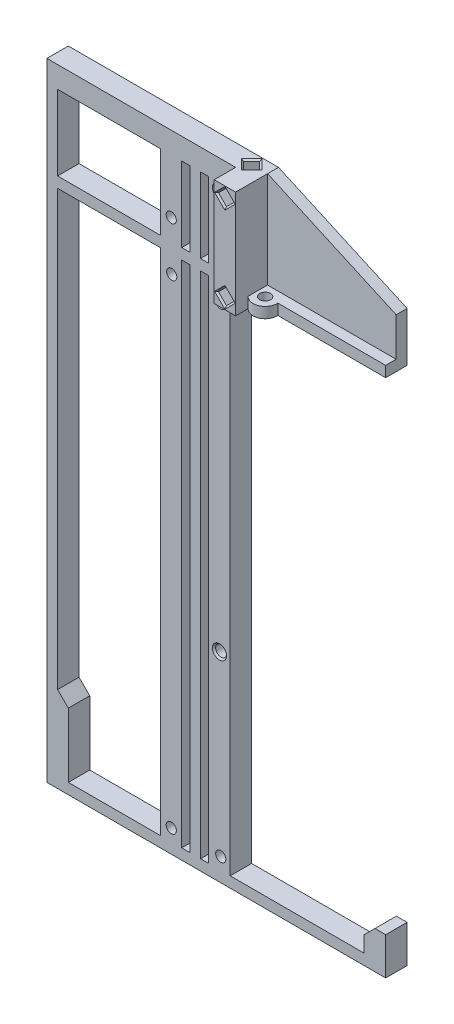
SolidWorks part; units mm, degrees
ref_plane "Front Plane" through (0, 0, 0) normal (0, 0, 1) x (1, 0, 0)
ref_plane "Top Plane" through (0, 0, 0) normal (0, 1, 0) x (1, 0, 0)
ref_plane "Right Plane" through (0, 0, 0) normal (1, 0, 0) x (0, 0, -1)
sketch "matx screw pattern" plane through (0, 0, 0) normal (0, 0, 1) x (1, 0, 0)
  line L1 (-121.92, 121.92) -> (121.92, 121.92) construction
  line L2 (-121.92, 121.92) -> (-121.92, -121.92) construction
  line L3 (-121.92, -121.92) -> (121.92, -121.92) construction
  line L4 (121.92, 121.92) -> (121.92, -121.92) construction
  point P4 (0, 121.92)
  point P6 (121.92, 0)
  point P7 (-111.76, -87.63)
  point P8 (-111.76, -41.91)
  point P9 (-88.9, 115.57)
  point P10 (43.18, -41.91)
  point P11 (43.18, -87.63)
  point P12 (43.18, -107.95)
  point P13 (115.57, -41.91)
  point P14 (115.57, 115.57)
  point P15 (43.18, 115.57)
  dimension "D1" = 243.84
  dimension "D2" = 10.16
  dimension "D3" = 22.86
  dimension "D4" = 227.33
  dimension "D5" = 154.94
  dimension "D6" = 203.2
  dimension "D7" = 45.72
  dimension "D8" = 20.32
  dimension "D9" = 34.29
sketch "Sketch1" plane through (0, 0, 0) normal (0, 0, 1) x (1, 0, 0)
  line L11 (47.4133, 127) -> (130.429, 127)
  line L12 (119.8033, 118.5333) -> (119.8033, 88.9)
  line L13 (181.229, -120.65) -> (47.4133, -120.65)
  line L14 (55.88, -116.4167) -> (55.88, -120.65) construction
  line L15 (55.88, -116.4167) -> (55.88, -91.0167)
  line L16 (51.6467, 118.5333) -> (92.1956, 118.5333)
  line L17 (51.6467, 118.5333) -> (51.6467, 88.9)
  line L18 (55.88, -116.4167) -> (92.1956, -116.4167)
  line L19 (111.3367, 118.5333) -> (111.3367, 88.9)
  line L20 (55.88, -91.0167) -> (51.6467, -86.7833)
  line L21 (119.8033, 118.5333) -> (121.9623, 118.5333)
  line L22 (121.9623, 118.5333) -> (121.9623, 88.9)
  line L26 (130.429, 127) -> (130.429, 88.9)
  line L27 (119.8033, -116.4167) -> (172.7623, -116.4167)
  line L29 (55.88, -116.4167) -> (47.4133, -116.4167) construction
  line L30 (47.4133, -120.65) -> (47.4133, 127)
  line L31 (172.7623, -116.4167) -> (172.7623, -110.0667)
  line L32 (172.7623, -110.0667) -> (176.9957, -105.8333)
  line L33 (92.1956, 118.5333) -> (92.1956, 88.9)
  line L34 (51.6467, 84.6667) -> (92.1956, 84.6667)
  line L35 (100.6623, -116.4167) -> (103.8828, -116.4167)
  line L36 (100.6623, 118.5333) -> (100.6623, 88.9)
  line L37 (100.6623, 118.5333) -> (103.8828, 118.5333)
  line L38 (100.6623, 84.6667) -> (103.8828, 84.6667)
  line L40 (119.8033, 84.6667) -> (181.229, 84.6667)
  line L41 (51.6467, 88.9) -> (92.1956, 88.9)
  line L42 (100.6623, 88.9) -> (103.8828, 88.9)
  line L43 (119.8033, 88.9) -> (121.9623, 88.9)
  line L44 (130.429, 88.9) -> (181.229, 88.9)
  line L45 (92.1956, -116.4167) -> (100.6623, -116.4167) construction
  line L46 (51.6467, 84.6667) -> (51.6467, -86.7833)
  line L47 (92.1956, 84.6667) -> (92.1956, -116.4167)
  line L48 (100.6623, 84.6667) -> (100.6623, -116.4167)
  line L49 (111.3367, 84.6667) -> (111.3367, -116.4167)
  line L50 (119.8033, 84.6667) -> (119.8033, -116.4167)
  line L54 (111.3367, -116.4167) -> (119.8033, -116.4167) construction
  line L55 (51.6467, 118.5333) -> (51.6467, 127) construction
  line L56 (172.7623, -116.4167) -> (181.229, -116.4167) construction
  line L57 (51.6467, -86.7833) -> (47.4133, -86.7833) construction
  line L58 (176.9957, -105.8333) -> (181.229, -105.8333)
  line L59 (51.6467, 88.9) -> (51.6467, 84.6667) construction
  line L60 (-121.92, 121.92) -> (121.92, 121.92) construction
  line L61 (121.9623, 88.9) -> (130.429, 88.9) construction
  line L62 (181.229, -105.8333) -> (181.229, -120.65)
  line L63 (103.8828, 118.5333) -> (103.8828, 88.9)
  line L64 (108.1161, 118.5333) -> (108.1161, 88.9)
  line L65 (108.1161, -116.4167) -> (111.3367, -116.4167)
  line L66 (108.1161, 88.9) -> (111.3367, 88.9)
  line L67 (108.1161, 84.6667) -> (111.3367, 84.6667)
  line L68 (103.8828, 84.6667) -> (103.8828, -116.4167)
  line L69 (108.1161, 84.6667) -> (108.1161, -116.4167)
  line L70 (108.1161, 118.5333) -> (111.3367, 118.5333)
  line L71 (103.8828, -116.4167) -> (108.1161, -116.4167) construction
  line L72 (181.229, 88.9) -> (181.229, 84.6667)
  point P0 (115.57, -116.4167)
  dimension "D2" = 4.2333
  dimension "D3" = 38.1
  dimension "D4" = 8.4667
  dimension "D5" = 4.2333
  dimension "D6" = 5.08
  dimension "D7" = 6.35
  dimension "D8" = 25.4
  dimension "D9" = 50.8
  dimension "D10" = 45
  dimension "D11" = 247.65
  dimension "D12" = 133.8157
  dimension "D13" = 40.549
extrude "Boss-Extrude1" add sketch "Sketch1" against normal blind 8.4667 from offset 9.525 offset against normal yes
sketch "Sketch9" plane through (0, 0, -17.9917) normal (0, 0, 1) x (1, 0, 0)
  line L3 (181.229, 88.9) -> (130.429, 88.9)
  line L4 (130.429, 127) -> (130.429, 88.9)
  line L7 (130.429, 127) -> (181.229, 104.14)
  line L9 (181.229, 104.14) -> (181.229, 88.9)
  dimension "D1" = 38.1
  dimension "D2" = 15.24
extrude "Boss-Extrude2" add sketch "Sketch9" along normal blind 4.318
sketch "Sketch16" plane through (0, 0, -9.525) normal (0, 0, 1) x (1, 0, 0)
  line L0 (119.8033, 84.6667) -> (181.229, 84.6667) construction
  line L1 (130.429, 127) -> (121.9623, 127)
  line L2 (130.429, 127) -> (130.429, 84.6667)
  line L3 (130.429, 84.6667) -> (121.9623, 84.6667)
  line L4 (121.9623, 127) -> (121.9623, 84.6667)
  line L5 (121.9623, 88.9) -> (121.9623, 118.5333) construction
extrude "Boss-Extrude3" add sketch "Sketch16" along normal blind 8.4667
sketch "Sketch18" plane through (0, 84.6667, 0) normal (0, -1, 0) x (-1, 0, 0)
  circle A0 centre (-133.889, 9.2517) radius 4.7625
  dimension "D1" = 9.525
extrude "Boss-Extrude4" add sketch "Sketch18" against normal up to surface (4.2333 mm away) up to face at (155.829, 88.9, -11.5993)
sketch "Sketch21" plane through (0, 88.9, 0) normal (0, 1, 0) x (1, 0, 0)
  arc A0 (130.429, 5.9791) -> (138.6436, 9.525) centre (133.889, 9.2517) ccw construction
  point P0 (133.889, 9.2517)
hole_wizard "#18 (0.1695) Diameter Hole3" positions "Sketch21" profile "Sketch22" hole size "#18" standard "ANSI Inch"
sketch "Sketch22" plane through (133.889, 88.9, -9.2517) normal (1, 0, 0) x (0, 0, 1)
  line L0 (0, 0) -> (0, 4.2333)
  line L1 (0, 4.2333) -> (2.1526, 4.2333)
  line L2 (2.1526, 4.2333) -> (2.1526, 0)
  line L5 (2.1526, 0) -> (0, 0)
  line L11 (0, -6.35) -> (0, 107.95) construction
  dimension "Thru Hole Dia." = 4.3053
  dimension "Thru Hole Depth" = 4.2333
sketch "Sketch5" plane through (0, 0, -9.525) normal (0, 0, 1) x (1, 0, 0)
  point P15 (115.57, 115.57)
  point P18 (115.57, -41.91)
hole_wizard "#18 (0.1695) Diameter Hole1" positions "Sketch5" profile "Sketch6" hole size "#18" standard "ANSI Inch" end condition through all
sketch "Sketch6" plane through (115.57, 115.57, -9.525) normal (1, 0, 0) x (0, -1, 0)
  line L0 (0, 0) -> (0, 8.4667)
  line L1 (0, 8.4667) -> (2.1526, 8.4667)
  line L2 (2.1526, 8.4667) -> (2.1526, 0.635)
  line L3 (2.1526, 0.635) -> (2.7876, 0)
  line L5 (2.7876, 0) -> (0, 0)
  line L6 (-2.1526, 0.635) -> (-2.7876, 0) construction
  line L11 (0, -6.35) -> (0, 107.95) construction
  dimension "Thru Hole Dia." = 4.3053
  dimension "Thru Hole Depth" = 8.4667
  dimension "Near C'Sink Dia." = 5.5753
  dimension "Near C'Sink Angle" = 90
sketch "Sketch2" plane through (0, -120.65, 0) normal (0, -1, 0) x (1, 0, 0)
  line L0 (173.8207, -13.7583) -> (176.9957, -10.5833)
  line L1 (173.8207, -13.7583) -> (176.9957, -16.9333)
  line L2 (176.9957, -10.5833) -> (180.1707, -13.7583)
  line L3 (176.9957, -16.9333) -> (180.1707, -13.7583)
  line L4 (173.8207, -13.7583) -> (180.1707, -13.7583) construction
  line L5 (176.9957, -10.5833) -> (176.9957, -16.9333) construction
  line L6 (48.4717, -13.7583) -> (51.6467, -10.5833)
  line L7 (48.4717, -13.7583) -> (51.6467, -16.9333)
  line L8 (51.6467, -10.5833) -> (54.8217, -13.7583)
  line L9 (51.6467, -16.9333) -> (54.8217, -13.7583)
  line L10 (48.4717, -13.7583) -> (54.8217, -13.7583) construction
  line L11 (51.6467, -10.5833) -> (51.6467, -16.9333) construction
  line L12 (47.4133, -17.9917) -> (47.4133, -9.525) construction
  line L14 (181.229, -17.9917) -> (181.229, -9.525) construction
  point P1 (176.9957, -13.7583)
  point P2 (51.6467, -13.7583)
  point P13 (47.4133, -13.7583)
  dimension "D1" = 6.35
  dimension "D2" = 4.2333
  dimension "D3" = 4.2333
extrude "bottom pins" cut sketch "Sketch2" against normal blind 6.35
sketch "Sketch3" plane through (47.4133, 0, 0) normal (-1, 0, 0) x (0, 0, 1)
  line L0 (-16.9333, 122.7667) -> (-13.7583, 125.9417)
  line L1 (-16.9333, 122.7667) -> (-13.7583, 119.5917)
  line L2 (-13.7583, 125.9417) -> (-10.5833, 122.7667)
  line L3 (-13.7583, 119.5917) -> (-10.5833, 122.7667)
  line L4 (-16.9333, 122.7667) -> (-10.5833, 122.7667) construction
  line L5 (-13.7583, 125.9417) -> (-13.7583, 119.5917) construction
  line L10 (-17.9917, 127) -> (-9.525, 127) construction
  line L11 (-17.9917, -120.65) -> (-9.525, -120.65) construction
  line L12 (-16.9333, -97.79) -> (-13.7583, -94.615)
  line L15 (-16.9333, -97.79) -> (-13.7583, -100.965)
  line L16 (-13.7583, -94.615) -> (-10.5833, -97.79)
  line L17 (-13.7583, -100.965) -> (-10.5833, -97.79)
  line L18 (-16.9333, -97.79) -> (-10.5833, -97.79) construction
  line L19 (-13.7583, -94.615) -> (-13.7583, -100.965) construction
  point P1 (-13.7583, 122.7667)
  point P9 (-13.7583, -97.79)
  point P18 (-13.7583, -120.65)
  dimension "D1" = 6.35
  dimension "D2" = 4.2333
  dimension "D3" = 22.86
extrude "rear pins" cut sketch "Sketch3" against normal blind 6.35
sketch "Sketch8" plane through (0, 0, -1.0583) normal (0, 0, 1) x (1, 0, 0)
  line L0 (123.0207, 88.9) -> (126.1957, 92.075)
  line L1 (123.0207, 88.9) -> (126.1957, 85.725)
  line L2 (126.1957, 92.075) -> (129.3707, 88.9)
  line L3 (126.1957, 85.725) -> (129.3707, 88.9)
  line L4 (123.0207, 88.9) -> (129.3707, 88.9) construction
  line L5 (126.1957, 92.075) -> (126.1957, 85.725) construction
  line L7 (121.9623, 88.9) -> (121.9623, 84.6667) construction
  line L9 (123.0207, 122.7667) -> (126.1957, 125.9417)
  line L10 (123.0207, 122.7667) -> (126.1957, 119.5917)
  line L11 (126.1957, 125.9417) -> (129.3707, 122.7667)
  line L12 (126.1957, 119.5917) -> (129.3707, 122.7667)
  line L13 (123.0207, 122.7667) -> (129.3707, 122.7667) construction
  line L14 (126.1957, 125.9417) -> (126.1957, 119.5917) construction
  line L15 (130.429, 127) -> (121.9623, 127) construction
  line L16 (119.8033, 84.6667) -> (121.9623, 84.6667) construction
  point P1 (126.1957, 88.9)
  point P10 (126.1957, 122.7667)
  dimension "D1" = 6.35
  dimension "D2" = 4.2333
  dimension "D3" = 4.2333
  dimension "D4" = 4.2333
extrude "left pins" cut sketch "Sketch8" against normal blind 6.35
sketch "Sketch24" plane through (0, 127, 0) normal (0, 1, 0) x (1, 0, 0)
  line L0 (120.904, 13.7583) -> (124.079, 16.9333)
  line L1 (120.904, 13.7583) -> (124.079, 10.5833)
  line L2 (124.079, 16.9333) -> (127.254, 13.7583)
  line L3 (124.079, 10.5833) -> (127.254, 13.7583)
  line L4 (120.904, 13.7583) -> (127.254, 13.7583) construction
  line L5 (124.079, 16.9333) -> (124.079, 10.5833) construction
  line L6 (130.429, 13.6737) -> (130.429, 1.0583) construction
  line L7 (130.429, 17.9917) -> (47.4133, 17.9917) construction
  line L8 (120.904, 13.7583) -> (124.079, 13.7583) construction
  point P1 (124.079, 13.7583)
  dimension "D1" = 6.35
  dimension "D2" = 6.35
  dimension "D3" = 4.2333
extrude "Cut-Extrude3" cut sketch "Sketch24" against normal blind 6.35
chamfer "Chamfer2" distance 0.635 angle 45 56 edges at (50.0592, -114.3, -12.1708) (53.2342, -114.3, -12.1708) (53.2342, -114.3, -15.3458) (50.0592, -114.3, -15.3458) (175.4082, -114.3, -12.1708) (178.5832, -114.3, -12.1708) (178.5832, -114.3, -15.3458) (175.4082, -114.3, -15.3458) (53.7633, -96.2025, -15.3458) (53.7633, -96.2025, -12.1708) (53.7633, -99.3775, -12.1708) (53.7633, -99.3775, -15.3458) (50.0592, -120.65, -12.1708) (50.0592, -120.65, -15.3458) (53.2342, -120.65, -15.3458) (53.2342, -120.65, -12.1708) (175.4082, -120.65, -15.3458) (175.4082, -120.65, -12.1708) (178.5832, -120.65, -12.1708) (178.5832, -120.65, -15.3458) (47.4133, -99.3775, -15.3458) (47.4133, -99.3775, -12.1708) (47.4133, -96.2025, -12.1708) (47.4133, -96.2025, -15.3458) (47.4133, 124.3542, -12.1708) (47.4133, 124.3542, -15.3458) (47.4133, 121.1792, -15.3458) (47.4133, 121.1792, -12.1708) (53.7633, 124.3542, -15.3458) (53.7633, 124.3542, -12.1708) (53.7633, 121.1792, -12.1708) (53.7633, 121.1792, -15.3458) (124.6082, 90.4875, -7.4083) (127.7832, 90.4875, -7.4083) (127.7832, 87.3125, -7.4083) (124.6082, 87.3125, -7.4083) (127.7832, 87.3125, -1.0583) (124.6082, 87.3125, -1.0583) (124.6082, 90.4875, -1.0583) (127.7832, 90.4875, -1.0583) (124.6082, 124.3542, -7.4083) (127.7832, 124.3542, -7.4083) (127.7832, 121.1792, -7.4083) (124.6082, 121.1792, -7.4083) (127.7832, 121.1792, -1.0583) (124.6082, 121.1792, -1.0583) (124.6082, 124.3542, -1.0583) (127.7832, 124.3542, -1.0583) (122.4915, 120.65, -15.3458) (125.6665, 120.65, -15.3458) (125.6665, 120.65, -12.1708) (122.4915, 120.65, -12.1708) (125.6665, 127, -15.3458) (125.6665, 127, -12.1708) (122.4915, 127, -12.1708) (122.4915, 127, -15.3458)
sketch "Sketch14" plane through (0, 0, -17.9917) normal (0, 0, -1) x (-1, 0, 0)
  point P0 (-116.078, 97.155)
  point P1 (-96.528, 97.155)
  point P3 (-96.728, 77.805)
  point P5 (-116.078, 77.605)
  point P7 (-116.078, -111.625)
  point P9 (-96.528, -111.625)
hole_wizard "#18 (0.1695) Diameter Hole2" positions "Sketch14" profile "Sketch15" hole size "#18" standard "ANSI Inch"
sketch "Sketch15" plane through (116.078, 97.155, -17.9917) normal (1, 0, 0) x (0, 1, 0)
  line L0 (0, 0) -> (0, 9.6754)
  line L1 (0, 9.6754) -> (2.1526, 8.382)
  line L2 (2.1526, 8.382) -> (2.1526, 0.635)
  line L3 (2.1526, 0.635) -> (2.7876, 0)
  line L5 (2.7876, 0) -> (0, 0)
  line L6 (-2.1526, 0.635) -> (-2.7876, 0) construction
  line L10 (0, 9.6754) -> (-2.1526, 8.382) construction
  line L11 (0, -6.35) -> (0, 107.95) construction
  dimension "Hole Dia." = 4.3053
  dimension "Hole Depth" = 8.382
  dimension "Near C'Sink Dia." = 5.5753
  dimension "Near C'Sink Angle" = 90
  dimension "Drill Angle" = 118
